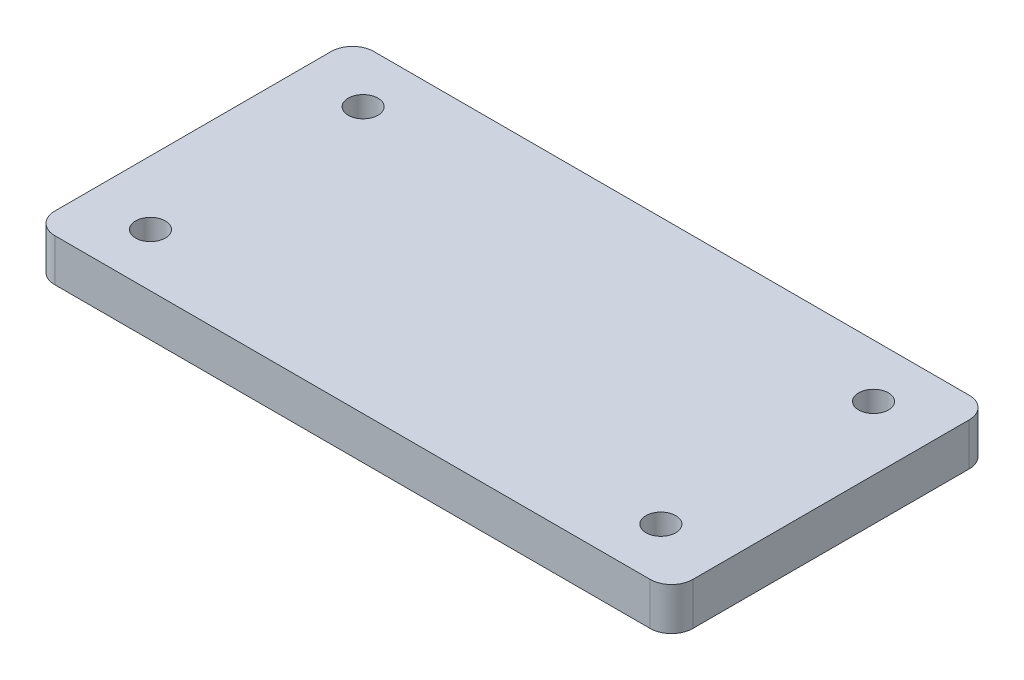
SolidWorks part; units mm, degrees
ref_plane "Front Plane" through (0, 0, 0) normal (0, 0, 1) x (1, 0, 0)
ref_plane "Top Plane" through (0, 0, 0) normal (0, 1, 0) x (1, 0, 0)
ref_plane "Right Plane" through (0, 0, 0) normal (1, 0, 0) x (0, 0, -1)
sketch "Sketch1" plane through (0, 0, 0) normal (0, 1, 0) x (1, 0, 0)
  line L1 (-150, -75) -> (150, -75)
  line L2 (-150, -75) -> (-150, 75)
  line L3 (-150, 75) -> (150, 75)
  line L4 (150, -75) -> (150, 75)
  line L5 (-150, -75) -> (150, 75) construction
  line L6 (-150, 75) -> (150, -75) construction
  point P0 (0, 0)
  dimension "D1" = 300
  dimension "D2" = 150
extrude "Boss-Extrude1" add sketch "Sketch1" along normal blind 20
fillet "Fillet1" radius 10 4 edges at (-150, 10, 75) (-150, 10, -75) (150, 10, -75) (150, 10, 75)
sketch "Sketch2" plane through (0, 20, 0) normal (0, 1, 0) x (1, 0, 0)
  line L1 (-120, -50) -> (120, -50)
  line L2 (-120, -50) -> (-120, 50)
  line L3 (-120, 50) -> (120, 50)
  line L4 (120, -50) -> (120, 50)
  line L5 (-120, -50) -> (120, 50) construction
  line L6 (-120, 50) -> (120, -50) construction
  point P0 (0, 0)
  dimension "D1" = 240
  dimension "D2" = 100
hole_wizard "Ø17.0 (17) Diameter Hole1" positions "3DSketch1" profile "Sketch3" hole size "Ø17.0" standard "ISO"
sketch3d "3DSketch1"
  point P0 (-120, 20, -50)
  point P3 (120, 20, -50)
  point P6 (120, 20, 50)
  point P9 (-120, 20, 50)
sketch "Sketch3" plane through (-120, 20, -50) normal (1, 0, 0) x (0, 0, 1)
  line L0 (0, 0) -> (0, 25.1073)
  line L1 (0, 25.1073) -> (8.5, 20)
  line L2 (8.5, 20) -> (8.5, 0)
  line L5 (8.5, 0) -> (0, 0)
  line L10 (0, 25.1073) -> (-8.5, 20) construction
  line L11 (0, -6.35) -> (0, 107.95) construction
  dimension "Hole Dia." = 17
  dimension "Hole Depth" = 20
  dimension "Drill Angle" = 118
hole_wizard "M16 Tapped Hole1" positions "3DSketch2" profile "Sketch4" tap size "M16" standard "ISO" end condition through all
sketch3d "3DSketch2"
  point P0 (-120, 20, -50)
  point P3 (120, 20, -50)
  point P6 (120, 20, 50)
  point P9 (-120, 20, 50)
sketch "Sketch4" plane through (-120, 20, -50) normal (1, 0, 0) x (0, 0, 1)
  line L0 (0, 0) -> (0, 20)
  line L1 (0, 20) -> (7, 20)
  line L2 (7, 20) -> (7, 0)
  line L5 (7, 0) -> (0, 0)
  line L11 (0, -6.35) -> (0, 107.95) construction
  dimension "Thru Tap Drill Dia." = 14
  dimension "Thru Tap Drill Depth" = 20
cosmetic thread "Hole Thread1" parameters "D2"=16
cosmetic thread "Hole Thread2" parameters "D2"=16
cosmetic thread "Hole Thread3" parameters "D2"=16
cosmetic thread "Hole Thread4" parameters "D2"=16
